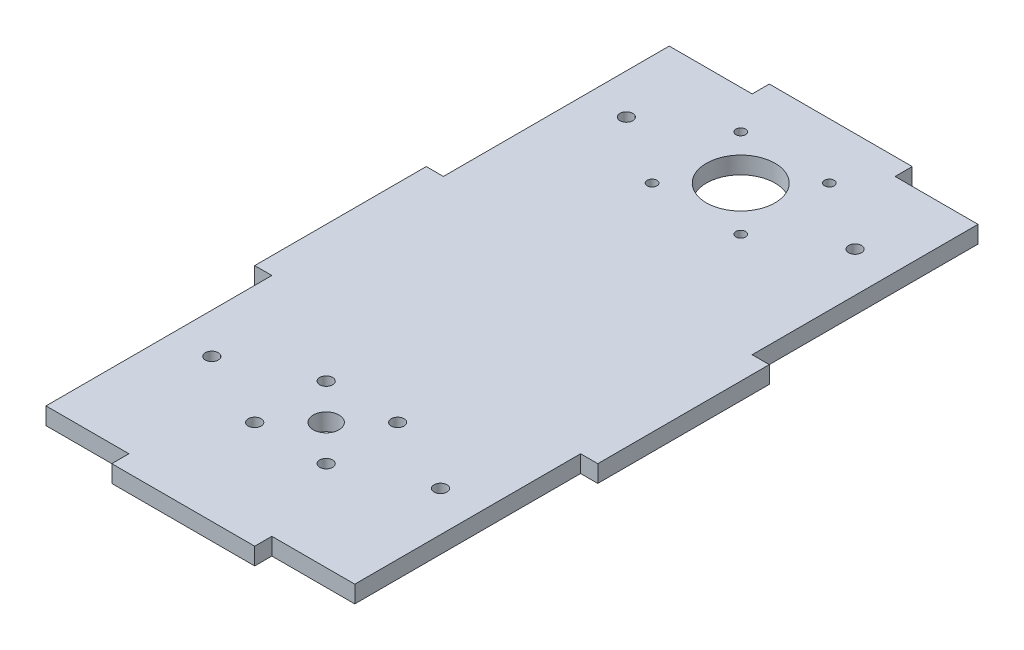
SolidWorks part; units mm, degrees
material "6061-T6 (SS)"
ref_plane "Alzado" through (0, 0, 0) normal (0, 0, 1) x (1, 0, 0)
ref_plane "Planta" through (0, 0, 0) normal (0, 1, 0) x (1, 0, 0)
ref_plane "Vista lateral" through (0, 0, 0) normal (1, 0, 0) x (0, 0, -1)
sketch "Croquis1" plane through (0, 0, 0) normal (0, 1, 0) x (1, 0, 0)
  line L0 (0, 0) -> (0, -115) construction
  line L1 (-54, -109) -> (-25, -109)
  line L2 (-54, -109) -> (-54, -30)
  line L3 (-54, 109) -> (-25, 109)
  line L4 (54, -109) -> (54, -30)
  line L5 (-54, -109) -> (54, 109) construction
  line L6 (-54, 109) -> (54, -109) construction
  line L7 (54, 30) -> (60, 30)
  line L9 (54, -30) -> (60, -30)
  line L10 (60, 30) -> (60, -30)
  line L11 (54, 30) -> (54, 109)
  line L12 (-54, -30) -> (-60, -30)
  line L13 (-54, 30) -> (-60, 30)
  line L14 (-60, 30) -> (-60, -30)
  line L15 (-54, 30) -> (-54, 109)
  line L16 (0, 0) -> (60, 0) construction
  line L18 (-25, 109) -> (-25, 115)
  line L19 (-25, 115) -> (25, 115)
  line L20 (25, 109) -> (25, 115)
  line L21 (25, -109) -> (25, -115)
  line L22 (-25, -115) -> (25, -115)
  line L23 (-25, -109) -> (-25, -115)
  line L24 (25, 109) -> (54, 109)
  line L25 (25, -109) -> (54, -109)
  circle A0 centre (0, -65) radius 4.5
  circle A1 centre (0, 80) radius 12
  point P0 (0, 0)
  point P12 (60, 0)
  point P21 (0, 115)
  dimension "D8" = 24
  dimension "D9" = 9
  dimension "D1" = 230
  dimension "D2" = 120
  dimension "D3" = 60
  dimension "D4" = 6
  dimension "D5" = 50
  dimension "D6" = 80
  dimension "D7" = 65
extrude "Saliente-Extruir1" add sketch "Croquis1" along normal mid plane 6
hole_wizard "Taladro de margen para M41" positions "Croquis2" profile "Croquis3" hole size "M4" standard "Ansi Metric" end condition up to next
sketch "Croquis2" plane through (0, 3, 0) normal (0, 1, 0) x (1, 0, 0)
  line L1 (-12.5, -52.5) -> (12.5, -52.5) construction
  line L2 (-12.5, -52.5) -> (-12.5, -77.5) construction
  line L3 (-12.5, -77.5) -> (12.5, -77.5) construction
  line L4 (12.5, -52.5) -> (12.5, -77.5) construction
  line L5 (-12.5, -52.5) -> (12.5, -77.5) construction
  line L6 (-12.5, -77.5) -> (12.5, -52.5) construction
  line L7 (12.5, -65) -> (-12.5, -65) construction
  line L13 (0, 92) -> (0, 68) construction
  circle A1 centre (0, -65) radius 4.5 construction
  circle A2 centre (0, 80) radius 12 construction
  point P0 (-12.5, -77.5)
  point P2 (-12.5, -52.5)
  point P4 (12.5, -52.5)
  point P6 (12.5, -77.5)
  point P42 (0, -65)
  dimension "D1" = 25
sketch "Croquis3" plane through (-12.5, 3, 77.5) normal (1, 0, 0) x (0, 0, 1)
  line L0 (0, 0) -> (0, 6)
  line L1 (0, 6) -> (2.25, 6)
  line L2 (2.25, 6) -> (2.25, 0)
  line L5 (2.25, 0) -> (0, 0)
  line L11 (0, -6.35) -> (0, 107.95) construction
  dimension "Diámetro de taladro hasta el siguiente" = 4.5
  dimension "Profundidad de taladro hasta el siguiente" = 6
hole_wizard "Taladro de margen para M42" positions "Croquis7" profile "Croquis8" hole size "M4" standard "Ansi Metric" end condition up to next
sketch "Croquis7" plane through (0, 3, 0) normal (0, 1, 0) x (1, 0, 0)
  line L0 (0, -60.5) -> (0, -69.5) construction
  line L2 (0, 92) -> (0, 68) construction
  circle A0 centre (0, -65) radius 4.5 construction
  circle A1 centre (0, 80) radius 12 construction
  point P0 (-40, 80)
  point P2 (-40, -65)
  point P13 (0, -65)
  point P21 (0, 80)
  point P22 (40, -65)
  point P23 (40, 80)
  dimension "D1" = 40
sketch "Croquis8" plane through (-40, 3, -80) normal (1, 0, 0) x (0, 0, 1)
  line L0 (0, 0) -> (0, 6)
  line L1 (0, 6) -> (2.25, 6)
  line L2 (2.25, 6) -> (2.25, 0)
  line L5 (2.25, 0) -> (0, 0)
  line L11 (0, -6.35) -> (0, 107.95) construction
  dimension "Diámetro de taladro hasta el siguiente" = 4.5
  dimension "Profundidad de taladro hasta el siguiente" = 6
hole_wizard "Taladro de margen para M32" positions "Croquis5" profile "Croquis6" hole size "M3" standard "Ansi Metric" end condition up to next
sketch "Croquis5" plane through (0, -3, 0) normal (0, -1, 0) x (-1, 0, 0)
  circle A0 centre (-15.5, 64.5) radius 1.25 construction
  circle A1 centre (-15.5, 95.5) radius 1.25 construction
  circle A2 centre (15.5, 64.5) radius 1.25 construction
  circle A3 centre (15.5, 95.5) radius 1.25 construction
  point P0 (-15.5, 64.5)
  point P2 (-15.5, 95.5)
  point P4 (15.5, 95.5)
  point P6 (15.5, 64.5)
sketch "Croquis6" plane through (15.5, -3, -64.5) normal (1, 0, 0) x (0, 0, -1)
  line L0 (0, 0) -> (0, 6)
  line L1 (0, 6) -> (1.7, 6)
  line L2 (1.7, 6) -> (1.7, 0)
  line L5 (1.7, 0) -> (0, 0)
  line L11 (0, -6.35) -> (0, 107.95) construction
  dimension "Diámetro de taladro hasta el siguiente" = 3.4
  dimension "Profundidad de taladro hasta el siguiente" = 6
